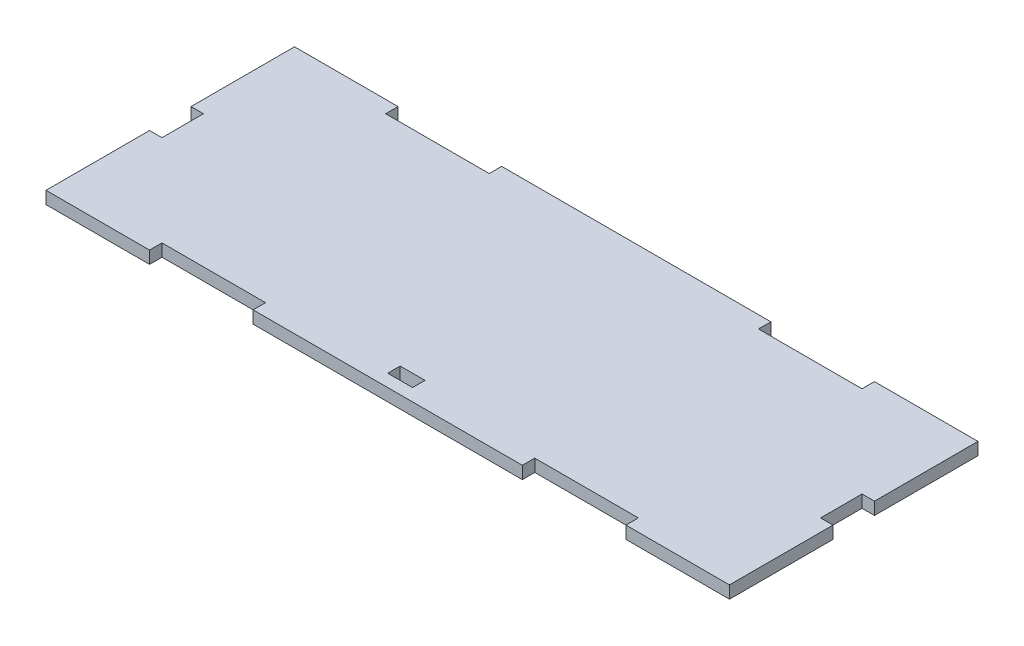
SolidWorks part; units mm, degrees
ref_plane "Front Plane" through (0, 0, 0) normal (0, 0, 1) x (1, 0, 0)
ref_plane "Top Plane" through (0, 0, 0) normal (0, 1, 0) x (1, 0, 0)
ref_plane "Right Plane" through (0, 0, 0) normal (1, 0, 0) x (0, 0, -1)
sketch "Sketch1" plane through (0, 0, 0) normal (0, 1, 0) x (1, 0, 0)
  line L0 (-57.5, 30) -> (-82.5, 30)
  line L1 (82.5, -30) -> (57.5, -30)
  line L2 (82.5, -30) -> (82.5, -5)
  line L3 (82.5, 30) -> (57.5, 30)
  line L4 (-82.5, -30) -> (-82.5, -5)
  line L5 (82.5, -30) -> (-82.5, 30) construction
  line L6 (82.5, 30) -> (-82.5, -30) construction
  line L7 (-82.5, 5) -> (-82.5, 30)
  line L8 (-57.5, 30) -> (-57.5, 27)
  line L9 (-57.5, 27) -> (-32.5, 27)
  line L10 (-32.5, 30) -> (-32.5, 27)
  line L12 (32.5, 30) -> (32.5, 27)
  line L13 (32.5, 27) -> (57.5, 27)
  line L14 (57.5, 30) -> (57.5, 27)
  line L15 (32.5, -30) -> (-32.5, -30)
  line L16 (-57.5, -30) -> (-57.5, -27)
  line L17 (-57.5, -27) -> (-32.5, -27)
  line L18 (-32.5, -30) -> (-32.5, -27)
  line L19 (82.5, 5) -> (82.5, 30)
  line L20 (32.5, -30) -> (32.5, -27)
  line L21 (32.5, -27) -> (57.5, -27)
  line L22 (57.5, -30) -> (57.5, -27)
  line L23 (-82.5, 5) -> (-79.5, 5)
  line L24 (-57.5, -30) -> (-82.5, -30)
  line L25 (-82.5, -5) -> (-79.5, -5)
  line L26 (-79.5, 5) -> (-79.5, -5)
  line L27 (82.5, 5) -> (79.5, 5)
  line L28 (32.5, 30) -> (-32.5, 30)
  line L29 (82.5, -5) -> (79.5, -5)
  line L30 (79.5, 5) -> (79.5, -5)
  line L31 (-3, -24) -> (3, -24)
  line L32 (-3, -24) -> (-3, -27)
  line L33 (-3, -27) -> (3, -27)
  line L34 (3, -24) -> (3, -27)
  line L35 (-3, -24) -> (3, -27) construction
  line L36 (-3, -27) -> (3, -24) construction
  point P0 (0, 0)
  point P21 (0, -25.5)
  dimension "D2" = 165
  dimension "D3" = 25
  dimension "D4" = 60
  dimension "D5" = 25
  dimension "D6" = 3
  dimension "D7" = 10
  dimension "D8" = 3
  dimension "D9" = 25
  dimension "D10" = 3
  dimension "D11" = 3
  dimension "D12" = 6
  dimension "D13" = 25
extrude "Boss-Extrude2" add sketch "Sketch1" along normal blind 3
